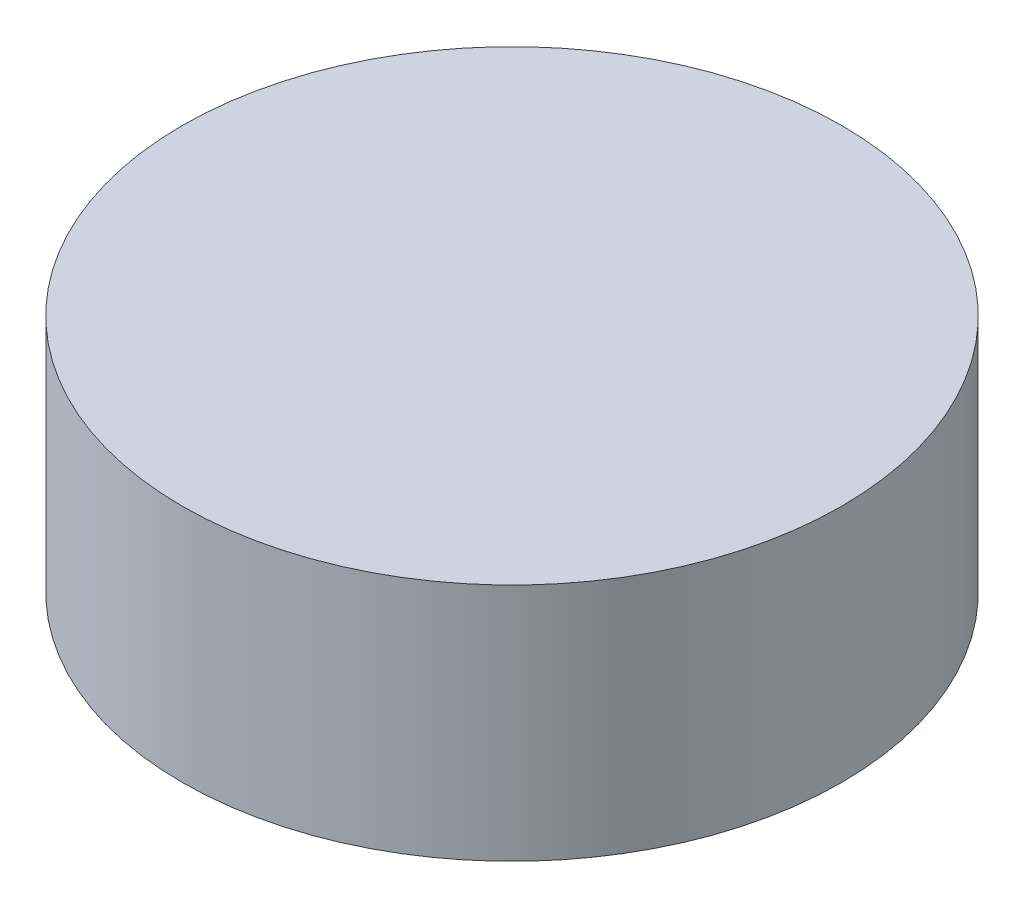
SolidWorks part; units mm, degrees
material "Copper"
ref_plane "Front Plane" through (0, 0, 0) normal (0, 0, 1) x (1, 0, 0)
ref_plane "Top Plane" through (0, 0, 0) normal (0, 1, 0) x (1, 0, 0)
ref_plane "Right Plane" through (0, 0, 0) normal (1, 0, 0) x (0, 0, -1)
sketch "Sketch1" plane through (0, 0, 0) normal (0, 1, 0) x (1, 0, 0)
  circle A0 centre (0, 0) radius 1.4
  dimension "D1" = 2.8
extrude "Boss-Extrude1" add sketch "Sketch1" along normal blind 1.016
